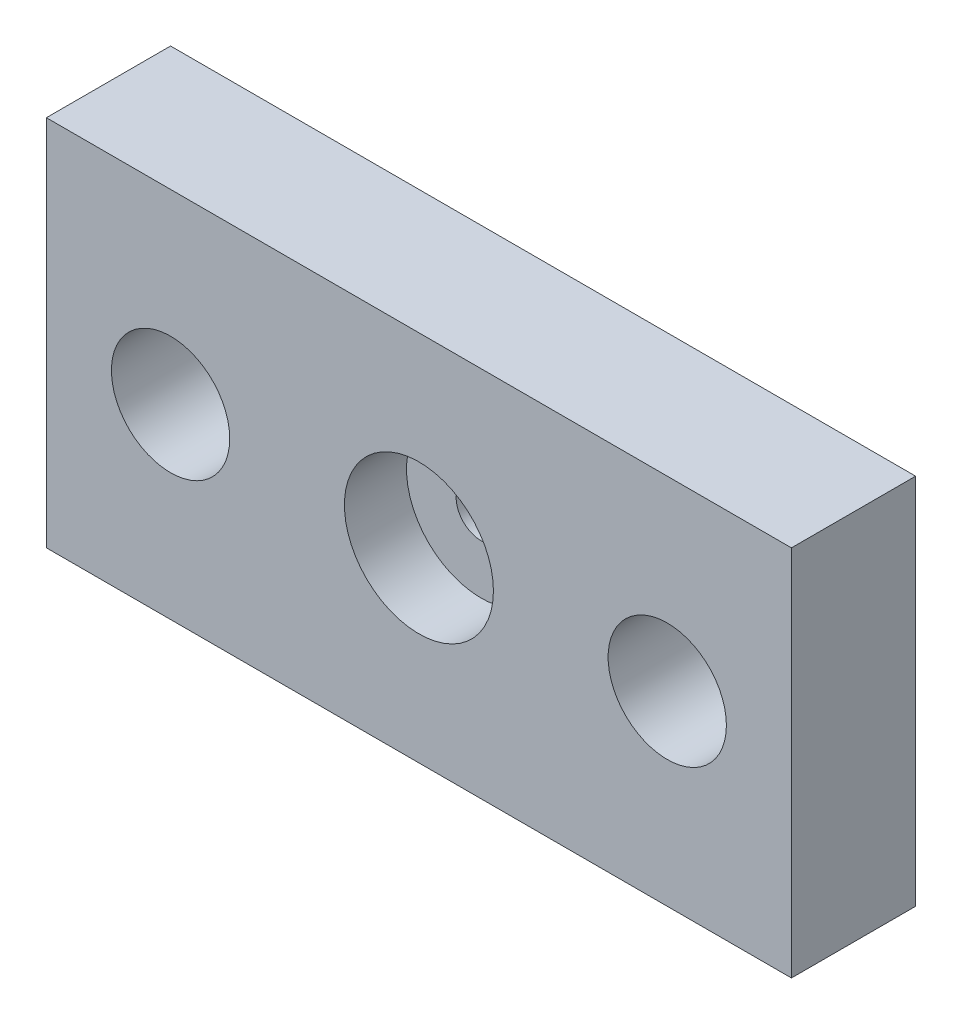
SolidWorks part; units mm, degrees
ref_plane "Front" through (0, 0, 0) normal (0, 0, 1) x (1, 0, 0)
ref_plane "Top" through (0, 0, 0) normal (0, 1, 0) x (1, 0, 0)
ref_plane "Right" through (0, 0, 0) normal (1, 0, 0) x (0, 0, -1)
sketch "Sketch1" plane through (0, 0, 0) normal (0, 0, 1) x (1, 0, 0)
  line L0 (-15, 0) -> (-10, 0) construction
  line L1 (-15, -7.5) -> (15, -7.5)
  line L2 (-15, -7.5) -> (-15, 7.5)
  line L3 (-15, 7.5) -> (15, 7.5)
  line L4 (15, -7.5) -> (15, 7.5)
  line L5 (-15, -7.5) -> (15, 7.5) construction
  line L6 (-15, 7.5) -> (15, -7.5) construction
  line L7 (-10, 0) -> (0, 0) construction
  line L8 (0, 0) -> (10, 0) construction
  line L9 (10, 0) -> (15, 0) construction
  circle A0 centre (0, 0) radius 1
  circle A1 centre (10, 0) radius 2.3813
  circle A2 centre (-10, 0) radius 2.3813
  point P0 (0, 0)
  dimension "D4" = 2
  dimension "D5" = 4.7625
  dimension "D1" = 30
  dimension "D2" = 15
  dimension "D3" = 20
extrude "Boss-Extrude1" add sketch "Sketch1" along normal blind 5
sketch "Sketch2" plane through (0, 0, 5) normal (0, 0, 1) x (1, 0, 0)
  circle A0 centre (0, 0) radius 3
  dimension "D1" = 6
extrude "Cut-Extrude1" cut sketch "Sketch2" against normal blind 2.5
